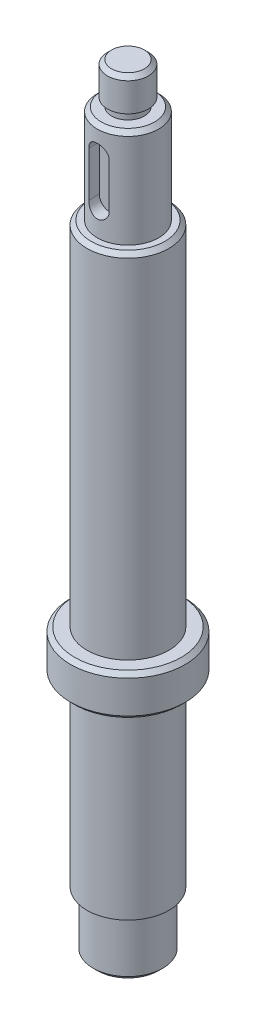
SolidWorks part; units mm, degrees
material "AISI 1045 Steel, cold drawn"
ref_plane "Front Plane" through (0, 0, 0) normal (0, 0, 1) x (1, 0, 0)
ref_plane "Top Plane" through (0, 0, 0) normal (0, 1, 0) x (1, 0, 0)
ref_plane "Right Plane" through (0, 0, 0) normal (1, 0, 0) x (0, 0, -1)
sketch "Sketch1" plane through (0, 0, 0) normal (0, 0, 1) x (1, 0, 0)
  line L0 (0, 0) -> (0, -189)
  line L1 (0, 0) -> (-5, 0)
  line L2 (-5, 0) -> (-5, -8)
  line L3 (-5, -8) -> (-4, -8)
  line L4 (-4, -8) -> (-4, -10)
  line L5 (-4, -10) -> (-7.5, -10)
  line L6 (-7.5, -10) -> (-7.5, -34)
  line L7 (-7.5, -34) -> (-10, -34)
  line L8 (-10, -34) -> (-10, -120)
  line L9 (-10, -120) -> (-14, -120)
  line L10 (-14, -120) -> (-14, -130)
  line L11 (-14, -130) -> (-10, -130)
  line L12 (-10, -130) -> (-10, -175)
  line L13 (0, -189) -> (-8.5, -189)
  line L14 (-8.5, -189) -> (-8.5, -175)
  line L15 (-10, -175) -> (-8.5, -175)
  dimension "D1" = 189
  dimension "D2" = 5
  dimension "D3" = 8
  dimension "D4" = 4
  dimension "D5" = 2
  dimension "D6" = 7.5
  dimension "D7" = 10
  dimension "D8" = 86
  dimension "D9" = 14
  dimension "D10" = 10
  dimension "D11" = 24
  dimension "D12" = 10
  dimension "D13" = 45
  dimension "D14" = 8.5
revolve "Revolve1" add sketch "Sketch1" angle 360 about L0
chamfer "Chamfer1" distance 1 angle 45 6 edges at (0, -189, 8.5) (0, -130, 14) (0, -120, 14) (0, -34, 10) (0, -10, 7.5) (0, 0, 5)
ref_plane "Plane1" through (0, 0, 7.5) normal (0, 0, 1) x (1, 0, 0)
sketch "Sketch2" plane through (0, 0, 7.5) normal (0, 0, 1) x (1, 0, 0)
  line L0 (0, -16.5) -> (0, -27.5) construction
  line L1 (2.5, -16.5) -> (2.5, -27.5)
  line L2 (-2.5, -16.5) -> (-2.5, -27.5)
  line L3 (9, -34) -> (-9, -34) construction
  arc A0 (2.5, -16.5) -> (-2.5, -16.5) centre (0, -16.5) ccw
  arc A1 (-2.5, -27.5) -> (2.5, -27.5) centre (0, -27.5) ccw
  point P3 (0, -22)
  dimension "D2" = 2.5
  dimension "D1" = 11
  dimension "D3" = 6.5
extrude "Cut-Extrude1" cut sketch "Sketch2" against normal blind 3
ref_plane "Plane2" through (0, 0, -10) normal (0, 0, 1) x (1, 0, 0)
sketch "Sketch3" plane through (0, 0, -10) normal (0, 0, 1) x (1, 0, 0)
  line L0 (0, -152) -> (0, -138) construction
  line L1 (-3, -152) -> (-3, -138)
  line L2 (3, -152) -> (3, -138)
  line L3 (-10, -130) -> (10, -130) construction
  arc A0 (-3, -152) -> (3, -152) centre (0, -152) ccw
  arc A1 (3, -138) -> (-3, -138) centre (0, -138) ccw
  point P3 (0, -145)
  dimension "D2" = 3
  dimension "D1" = 14
  dimension "D3" = 8
extrude "Cut-Extrude2" cut sketch "Sketch3" along normal blind 3.5
